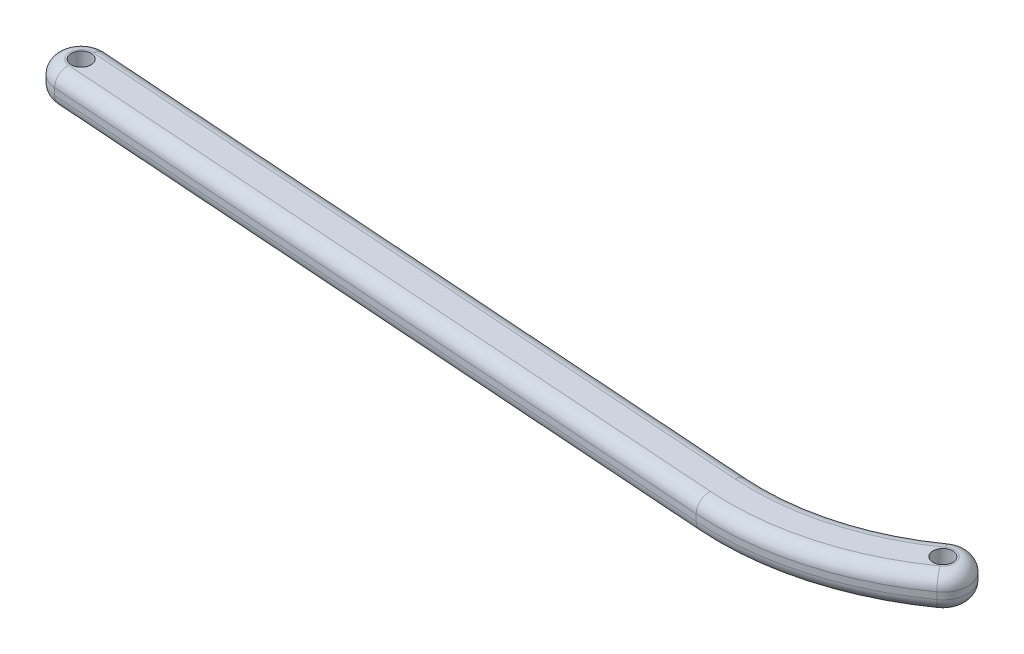
SolidWorks part; units mm, degrees
material "ABS PC"
ref_plane "Alzado" through (0, 0, 0) normal (1, 0, 0) x (0, 1, 0)
ref_plane "Planta" through (0, 0, 0) normal (0, 0, 1) x (0, 1, 0)
ref_plane "Vista lateral" through (0, 0, 0) normal (0, 1, 0) x (-1, 0, 0)
sketch "Croquis1" plane through (0, 0, 0) normal (0, 1, 0) x (-1, 0, 0)
  line L0 (0, 0) -> (260, 0) construction
  line L1 (51.8656, 14.5542) -> (260, 0) construction
  line L2 (52.3888, 22.0359) -> (260.5232, 7.4817)
  line L3 (51.3425, 7.0724) -> (259.4768, -7.4817)
  line L4 (260, 0) -> (51.8656, 14.5542) construction
  line L9 (130, -7.5) -> (130, 0) construction
  line L10 (0, 0) -> (46.2851, -65.251) construction
  line L11 (46.2851, -65.251) -> (51.8656, 14.5542) construction
  circle A0 centre (0, 0) radius 3
  circle A1 centre (260, 0) radius 3
  arc A2 (4.3392, -6.1173) -> (51.3425, 7.0724) centre (46.2851, -65.251) cw
  arc A16 (259.4768, -7.4817) -> (260.5232, 7.4817) centre (260, 0) ccw
  arc A17 (0, 0) -> (51.8656, 14.5542) centre (46.2851, -65.251) cw construction
  arc A20 (0, 0) -> (51.8656, 14.5542) centre (46.2851, -65.251) cw construction
  arc A25 (-4.3392, 6.1173) -> (4.3392, -6.1173) centre (0, 0) ccw
  arc A27 (-4.3392, 6.1173) -> (52.3888, 22.0359) centre (46.2851, -65.251) cw
  arc A28 (4.3392, -6.1173) -> (51.3425, 7.0724) centre (46.2851, -65.251) cw construction
  point P12 (189.4945, 12.5454)
  point P24 (58.428, 23.6733)
  dimension "D3" = 6
  dimension "D2" = 80
  dimension "D4" = 7.5
  dimension "D1" = 260
  dimension "D5" = 4
extrude "Saliente-Extruir1" add sketch "Croquis1" along normal mid plane 10
fillet "Redondeo7" radius 4 12 edges at (-156.456, 5, 14.7588) (-267.4817, 5, -0.5232) (-155.4097, 5, -0.2046) (6.1173, 5, -4.3392) (-156.456, -5, 14.7588) (-267.4817, -5, -0.5232) (-155.4097, -5, -0.2046) (6.1173, -5, -4.3392) (-22.6446, -5, 18.995) (-26.6973, -5, 4.5528) (-22.6446, 5, 18.995) (-26.6973, 5, 4.5528)
equation "\"L1\"=250"
equation "\"ancho\"= 15"
equation "\"esp\"= 10"
equation "\"agujeros\"= 6"
equation "\"L2\"=260"
equation "\"D1@Croquis1\"=\"L2\""
equation "\"D3@Croquis1\"=\"agujeros\""
equation "\"D1@Saliente-Extruir1\"=\"esp\""
